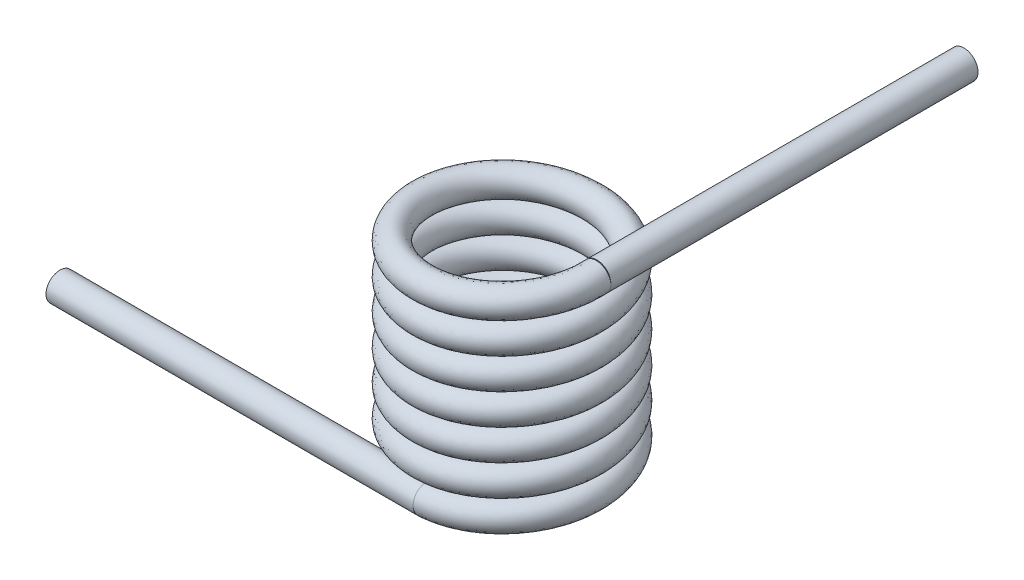
SolidWorks part; units mm, degrees
material "Plain Carbon Steel"
ref_plane "Front Plane" through (0, 0, 0) normal (0, 0, 1) x (1, 0, 0)
ref_plane "Top Plane" through (0, 0, 0) normal (0, 1, 0) x (1, 0, 0)
ref_plane "Right Plane" through (0, 0, 0) normal (1, 0, 0) x (0, 0, -1)
sketch "Sketch1" plane through (0, 0, 0) normal (0, 1, 0) x (1, 0, 0)
  circle A0 centre (0, 0) radius 1.3885
  dimension "D1" = 2.777
curve "Helix/Spiral1" pitch 0.5029 height 3.143 turns 6.25
ref_plane "Plane1" through (0, 3.143, 0) normal (0, 1, 0) x (1, 0, 0)
sketch "Sketch2" plane through (0, 3.143, 0) normal (0, 1, 0) x (1, 0, 0)
  line L0 (1.3885, 0) -> (1.3885, 6)
  circle A0 centre (0, 0) radius 1.3885 construction
  dimension "D1" = 6
sketch "Sketch3" plane through (0, 0, 0) normal (0, 1, 0) x (1, 0, 0)
  line L0 (0, -1.3885) -> (-6, -1.3885)
  circle A0 centre (0, 0) radius 1.3885 construction
  dimension "D1" = 6
sweep "Sweep1" add path "Sketch3" circular profile diameter 0.457 parameters "D3"=0.457
sweep "Sweep2" add path "Sketch2" circular profile diameter 0.457 parameters "D3"=0.457
sweep "Sweep7" add path "Helix/Spiral1" parameters "D3"=0.457
